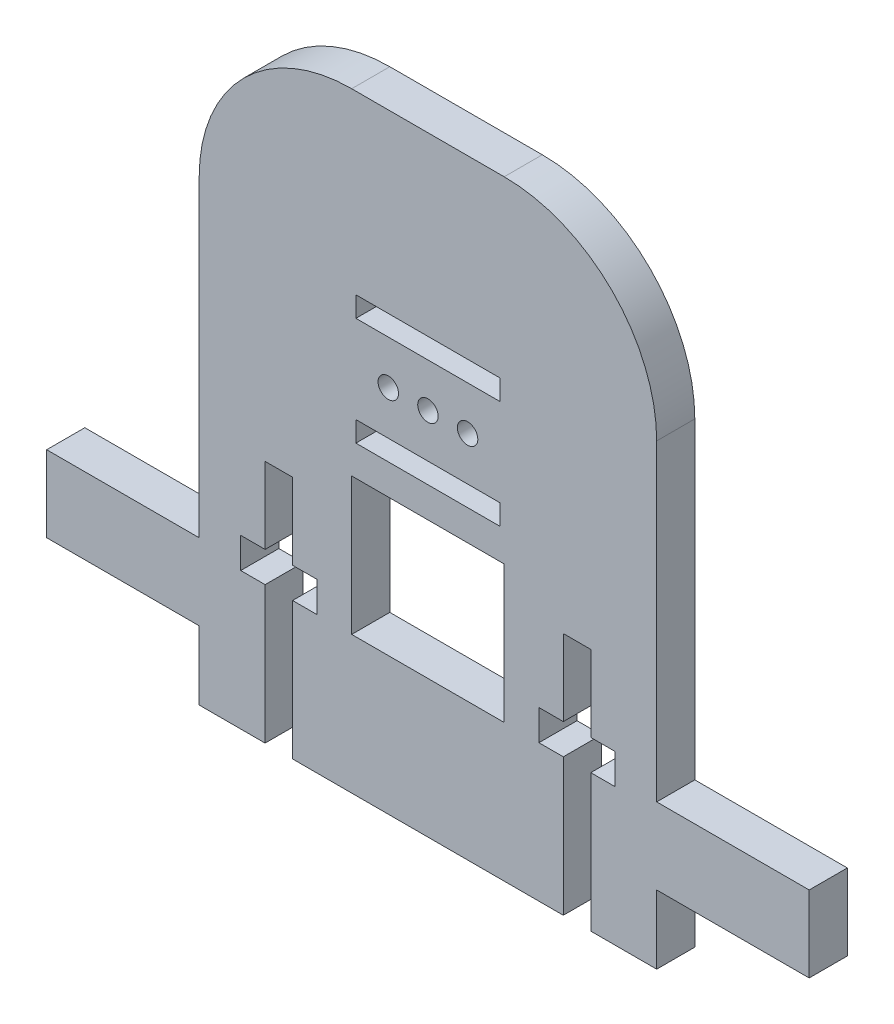
SolidWorks part; units mm, degrees
ref_plane "Front Plane" through (0, 0, 0) normal (0, 0, 1) x (1, 0, 0)
ref_plane "Top Plane" through (0, 0, 0) normal (0, 1, 0) x (1, 0, 0)
ref_plane "Right Plane" through (0, 0, 0) normal (1, 0, 0) x (0, 0, -1)
sketch "Sketch1" plane through (0, 0, 0) normal (0, 0, 1) x (1, 0, 0)
  line L0 (0, -1.7463) -> (0, 1.7463) construction
  line L1 (19.05, -25.4) -> (-19.05, -25.4)
  line L2 (19.05, -25.4) -> (19.05, -19.685)
  line L3 (19.05, 25.4) -> (-19.05, 25.4)
  line L4 (-19.05, -25.4) -> (-19.05, -19.685)
  line L5 (19.05, -25.4) -> (-19.05, 25.4) construction
  line L6 (19.05, 25.4) -> (-19.05, -25.4) construction
  line L7 (-19.05, -19.685) -> (-31.75, -19.685)
  line L9 (-19.05, -13.335) -> (-31.75, -13.335)
  line L10 (-31.75, -19.685) -> (-31.75, -13.335)
  line L11 (31.75, -19.685) -> (31.75, -13.335)
  line L12 (19.05, -13.335) -> (31.75, -13.335)
  line L14 (19.05, -19.685) -> (31.75, -19.685)
  line L15 (-19.05, -13.335) -> (-19.05, 25.4)
  line L16 (19.05, -13.335) -> (19.05, 25.4)
  point P0 (0, 0)
  dimension "D1" = 38.1
  dimension "D2" = 50.8
  dimension "D3" = 12.7
  dimension "D4" = 6.35
  dimension "D5" = 5.715
extrude "Boss-Extrude1" add sketch "Sketch1" along normal blind 3.175
fillet "Fillet1" radius 12.7 2 edges at (19.05, 25.4, 1.5875) (-19.05, 25.4, 1.5875)
sketch "Sketch2" plane through (0, 0, 0) normal (0, 0, 1) x (1, 0, 0)
  line L0 (-19.05, -25.4) -> (19.05, -25.4) construction
  line L1 (0, -1.7463) -> (0, 1.7463) construction
  line L2 (-6, 9.015) -> (6, 10.715) construction
  line L3 (-6, 1.715) -> (6, 1.715)
  line L4 (-6, 1.715) -> (-6, 0.015)
  line L5 (-6, 0.015) -> (6, 0.015)
  line L6 (6, 1.715) -> (6, 0.015)
  line L7 (-6, 1.715) -> (6, 0.015) construction
  line L8 (-6, 0.015) -> (6, 1.715) construction
  line L9 (-6, 10.715) -> (6, 10.715)
  line L10 (-6, 9.015) -> (6, 9.015)
  line L11 (6, 10.715) -> (6, 9.015)
  line L12 (-6, 10.715) -> (6, 9.015) construction
  line L13 (-6, 10.715) -> (-6, 9.015)
  circle A0 centre (0, 5.365) radius 0.85
  circle A1 centre (-3.302, 5.365) radius 0.85
  circle A2 centre (3.302, 5.365) radius 0.85
  point P11 (0, 0.865)
  point P16 (0, 9.865)
  dimension "D2" = 1.7
  dimension "D1" = 30.765
  dimension "D4" = 1.7
  dimension "D5" = 12
  dimension "D6" = 1.7
  dimension "D7" = 12
  dimension "D8" = 4.5
  dimension "D9" = 4.5
  dimension "D3" = 2
extrude "Cut-Extrude1" cut sketch "Sketch2" along normal through all
sketch "Sketch3" plane through (0, 0, 0) normal (0, 0, 1) x (1, 0, 0)
  line L0 (-6, 0.015) -> (6, 0.015) construction
  line L1 (-13.5598, -5.08) -> (-11.2738, -5.08)
  line L2 (-13.5598, -5.08) -> (-13.5598, -25.4)
  line L3 (-13.5598, -25.4) -> (-11.2738, -25.4)
  line L4 (-11.2738, -5.08) -> (-11.2738, -25.4)
  line L5 (-13.5598, -5.08) -> (-11.2738, -25.4) construction
  line L6 (-13.5598, -25.4) -> (-11.2738, -5.08) construction
  line L7 (-6.35, -2.525) -> (6.35, -2.525)
  line L8 (-19.05, -25.4) -> (19.05, -25.4) construction
  line L9 (-6.35, -2.525) -> (-6.35, -13.955)
  line L10 (-15.5918, -11.43) -> (-9.2418, -11.43)
  line L11 (-15.5918, -11.43) -> (-15.5918, -13.97)
  line L12 (-15.5918, -13.97) -> (-9.2418, -13.97)
  line L13 (-9.2418, -11.43) -> (-9.2418, -13.97)
  line L14 (-15.5918, -11.43) -> (-9.2418, -13.97) construction
  line L15 (-15.5918, -13.97) -> (-9.2418, -11.43) construction
  line L16 (-6.35, -13.955) -> (6.35, -13.955)
  line L17 (6.35, -2.525) -> (6.35, -13.955)
  line L18 (-6.35, -2.525) -> (6.35, -13.955) construction
  line L19 (-6.35, -13.955) -> (6.35, -2.525) construction
  line L20 (0, -1.7463) -> (0, 1.7463) construction
  line L21 (15.5918, -13.97) -> (9.2418, -11.43) construction
  line L22 (15.5918, -11.43) -> (9.2418, -13.97) construction
  line L23 (13.5598, -25.4) -> (11.2738, -5.08) construction
  line L24 (13.5598, -5.08) -> (11.2738, -25.4) construction
  line L25 (9.2418, -11.43) -> (9.2418, -13.97)
  line L26 (15.5918, -13.97) -> (9.2418, -13.97)
  line L27 (15.5918, -11.43) -> (15.5918, -13.97)
  line L28 (15.5918, -11.43) -> (9.2418, -11.43)
  line L29 (11.2738, -5.08) -> (11.2738, -25.4)
  line L30 (13.5598, -25.4) -> (11.2738, -25.4)
  line L31 (13.5598, -5.08) -> (13.5598, -25.4)
  line L32 (13.5598, -5.08) -> (11.2738, -5.08)
  point P0 (-12.4168, -15.24)
  point P8 (-12.4168, -12.7)
  point P18 (0, -8.24)
  point P33 (12.4168, -12.7)
  point P34 (12.4168, -15.24)
  dimension "D1" = 20.32
  dimension "D2" = 2.286
  dimension "D3" = 12.7
  dimension "D4" = 2.54
  dimension "D5" = 6.35
  dimension "D6" = 12.7
  dimension "D7" = 11.43
  dimension "D8" = 2.54
extrude "Cut-Extrude2" cut sketch "Sketch3" along normal through all contours L3 L4 L1 L2 | L13 L12 L11 L10 | L9 L7 L17 L16 | L29 L30 L31 L32 | L25 L26 L27 L28
equation "\"motor offset\"= 6mm"
equation "\"thickness0.25\"= 0.225in"
equation "\"thickness0.125\"= 0.122in"
